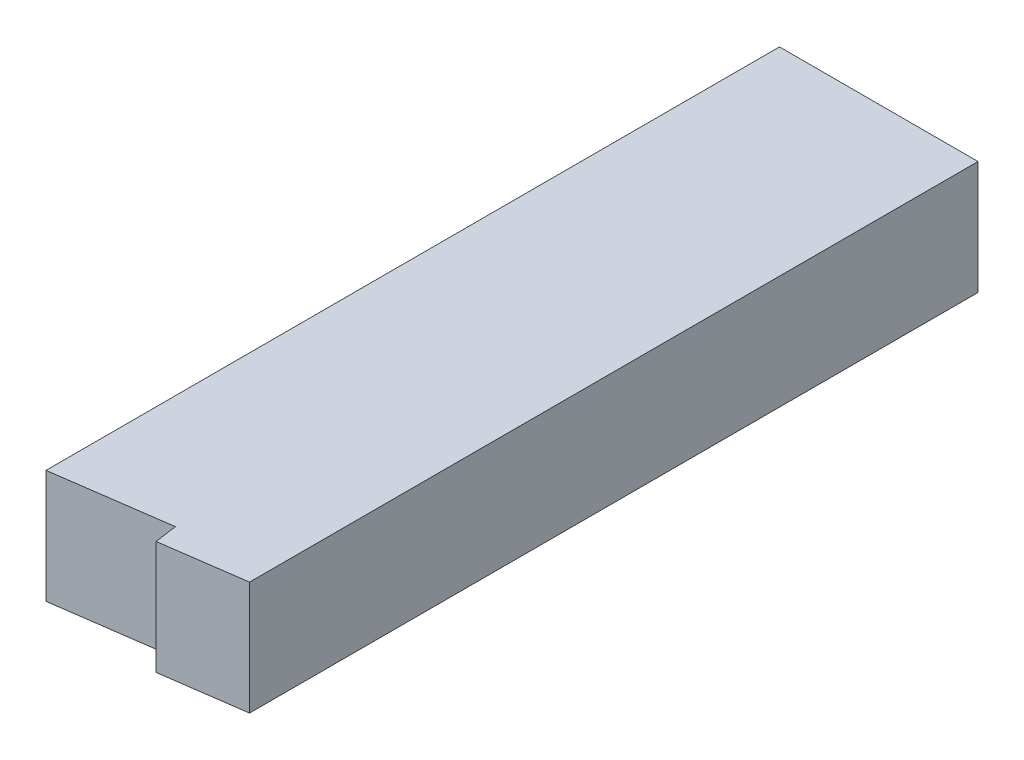
SolidWorks part; units mm, degrees
material "Pine"
ref_plane "X-Y Datum" through (0, 0, 0) normal (0, 0, 1) x (1, 0, 0)
ref_plane "X-Z Datum" through (0, 0, 0) normal (0, 1, 0) x (1, 0, 0)
ref_plane "Y-Z Datum" through (0, 0, 0) normal (1, 0, 0) x (0, 0, -1)
sketch "Sketch1" plane through (0, 0, 0) normal (0, 0, 1) x (1, 0, 0)
  line L1 (-50.8, 25.4) -> (50.8, 25.4)
  line L2 (-50.8, 25.4) -> (-50.8, -25.4)
  line L3 (-50.8, -25.4) -> (50.8, -25.4)
  line L4 (50.8, 25.4) -> (50.8, -25.4)
  line L5 (-50.8, 25.4) -> (50.8, -25.4) construction
  line L6 (-50.8, -25.4) -> (50.8, 25.4) construction
  point P0 (0, 0)
  dimension "D1" = 101.6
  dimension "D2" = 50.8
extrude "Boss-Extrude1" add sketch "Sketch1" along normal blind 331.3657
sketch "Sketch2" plane through (0, 25.4, 0) normal (0, 1, 0) x (1, 0, 0)
  line L1 (-50.8, -328.4441) -> (0, -321.3046)
  line L3 (1.414, -331.3657) -> (50.8, -324.425)
  line L4 (50.8, -331.3657) -> (50.8, 0) construction
  line L5 (50.8, -324.425) -> (50.8, -331.3657)
  line L6 (50.8, -331.3657) -> (1.414, -331.3657)
  line L7 (0, -321.3046) -> (1.414, -331.3657)
  line L8 (-50.8, -331.3657) -> (-50.8, 0) construction
  line L9 (-50.8, -331.3657) -> (50.8, -331.3657) construction
  line L10 (-50.8, -328.4441) -> (-50.8, -331.3657)
  line L11 (-50.8, -331.3657) -> (1.414, -331.3657)
  line M2 (-50.8, 0) -> (-50.8, -331.3657)
  line M3 (-50.8, -331.3657) -> (50.8, -331.3657)
  line M4 (50.8, -331.3657) -> (50.8, 0)
  dimension "D1" = 10.16
  dimension "D4" = 8
  dimension "D6" = 50.8
extrude "Cut-Extrude1" cut sketch "Sketch2" against normal through all both and the other way through all contours L3 M3 M4 | L7 L1 M2 M3
sketch "Sketch3" plane through (0, -25.4, 0) normal (0, -1, 0) x (1, 0, 0)
  line L0 (-50.8, 0) -> (50.8, 0) construction
  line L1 (50.8, 355.6) -> (38.1, 355.6)
  line L2 (50.8, 355.6) -> (50.8, 0)
  line L3 (50.8, 0) -> (38.1, 0)
  line L4 (38.1, 355.6) -> (38.1, 0)
  line L5 (-50.8, 328.4441) -> (-50.8, 0) construction
  point P9 (0, 0)
  point P10 (0, 0)
  point P11 (38.1, 333.3368)
  dimension "D1" = 88.9
  dimension "D2" = 355.6
extrude "Cut-Extrude2" cut sketch "Sketch3" against normal through all both
